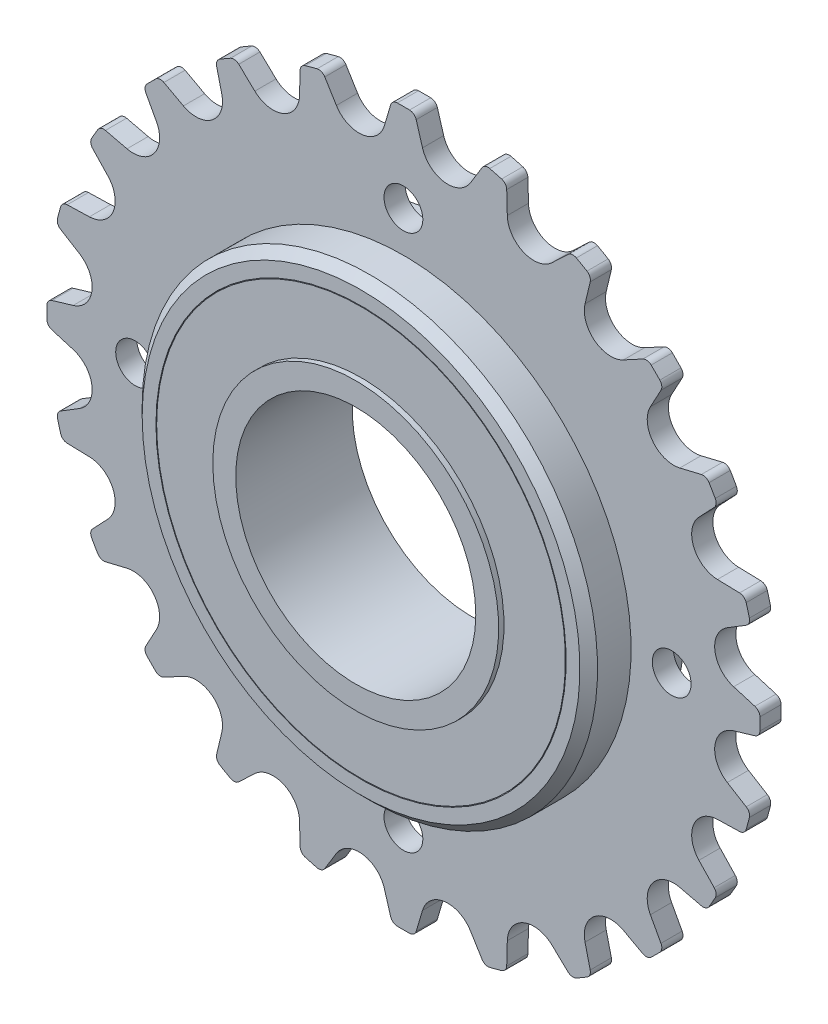
SolidWorks part; units mm, degrees
ref_plane "Front Plane" through (0, 0, 0) normal (0, 0, 1) x (1, 0, 0)
ref_plane "Top Plane" through (0, 0, 0) normal (0, 1, 0) x (1, 0, 0)
ref_plane "Right Plane" through (0, 0, 0) normal (1, 0, 0) x (0, 0, -1)
sketch "Sketch1" plane through (0, 0, 0) normal (0, 1, 0) x (1, 0, 0)
  line L0 (0, 16.3992) -> (0, -18.1929) construction
sketch "Sketch2" plane through (0, 0, 0) normal (0, 1, 0) x (1, 0, 0)
  line L1 (20.25, -7.5) -> (28.95, -7.5)
  line L2 (28.95, -7.5) -> (28.95, -2.5)
  line L3 (28.95, -2.5) -> (29.05, -2.5)
  line L4 (29.05, -2.5) -> (29.05, -7.5)
  line L5 (29.05, -7.5) -> (31, -7.5)
  line L6 (31, -7.5) -> (32.25, -6.25)
  line L7 (32.25, -6.25) -> (32.25, -1.5)
  line L8 (32.25, -1.5) -> (50.5, -1.5)
  line L9 (50.5, -1.5) -> (50.5, 1.5)
  line L10 (50.5, 1.5) -> (32.25, 1.5)
  line L11 (32.25, 1.5) -> (32.25, 6.25)
  line L12 (32.25, 6.25) -> (31, 7.5)
  line L13 (31, 7.5) -> (29.05, 7.5)
  line L14 (29.05, 7.5) -> (29.05, 2.5)
  line L16 (28.95, 2.5) -> (28.95, 7.5)
  line L17 (28.95, 7.5) -> (20.25, 7.5)
  line L18 (0, 0) -> (10.25, 0) construction
  line L19 (29.05, 2.5) -> (28.95, 2.5)
  line L20 (20.25, 7.5) -> (20.25, 8.25)
  line L21 (20.25, 8.25) -> (10.25, 8.25)
  line L22 (10.25, 8.25) -> (10.25, -8.25)
  line L23 (10.25, -8.25) -> (20.25, -8.25)
  line L24 (20.25, -8.25) -> (20.25, -7.5)
  line L26 (0, 200016.3992) -> (0, -200018.1929) construction
  point P27 (28.95, 5)
  dimension "D1" = 15
  dimension "D2" = 20.25
  dimension "D3" = 3
  dimension "D4" = 10
  dimension "D5" = 0.75
  dimension "D6" = 28.95
  dimension "D7" = 0.1
  dimension "D8" = 31
  dimension "D9" = 32.25
  dimension "D10" = 5
  dimension "D11" = 135
  dimension "D12" = 50.5
revolve "Revolve1" add sketch "Sketch2" angle 360 about L0
hole_wizard "M36x2.0 Tapped Hole2" positions "Sketch5" profile "Sketch6" tap size "M36x2.0" standard "ANSI Metric" end condition through all
sketch "Sketch5" plane through (0, 0, 8.25) normal (0, 0, 1) x (1, 0, 0)
  point P0 (0, 0)
sketch "Sketch6" plane through (0, 0, 8.25) normal (1, 0, 0) x (0, -1, 0)
  line L0 (0, 0) -> (0, 16.5)
  line L1 (0, 16.5) -> (17, 16.5)
  line L2 (17, 16.5) -> (17, 0)
  line L5 (17, 0) -> (0, 0)
  line L11 (0, -6.35) -> (0, 107.95) construction
  dimension "Thru Tap Drill Dia." = 34
  dimension "Thru Tap Drill Depth" = 16.5
cosmetic thread "Hole Thread1" parameters "D2"=36
sketch "Sketch7" plane through (0, 0, 0) normal (0, 0, 1) x (1, 0, 0)
  line L0 (0, 0) -> (5.8084, 44.1193) construction
  line L1 (6.7874, 51.5551) -> (6.2979, 47.8372) construction
  line L2 (0, 0) -> (0, 50.5) construction
  line L4 (9.4935, 45.875) -> (11.5164, 49.1693)
  line L5 (2.7033, 46.7689) -> (1.602, 50.4746)
  line L6 (1.602, 50.4746) -> (11.5164, 49.1693) construction
  line L7 (5.8084, 44.1193) -> (6.2979, 47.8372) construction
  circle A0 centre (6.2979, 47.8372) radius 3.75
  circle A1 centre (0, 0) radius 50.5 construction
  circle A2 centre (0, 0) radius 50.5
  dimension "D2" = 7.5
  dimension "D4" = 7.5
  dimension "D1" = 44.5
  dimension "D3" = 10
extrude "Cut-Extrude1" cut sketch "Sketch7" against normal through all both and the other way through all contours L4 A2 L5 A0 | A0 | A0 A2 L5
fillet "Fillet1" radius 1 2 edges at (11.5164, 49.1693, 0) (1.602, 50.4746, 0)
pattern_circular "CirPattern1" count 24 over 360 about axis through (0, 0, 0) along (0, 0, 1) of "Cut-Extrude1", "Fillet1"
sketch "Sketch8" plane through (0, 0, 0) normal (0, 0, 1) x (1, 0, 0)
  line L0 (0, 0) -> (0, 38) construction
  circle A1 centre (0, 38) radius 2.75
  circle A2 centre (38, 0) radius 2.75
  circle A3 centre (0, -38) radius 2.75
  circle A4 centre (-38, 0) radius 2.75
  point P14 (0, 0)
  dimension "D1" = 38
  dimension "D2" = 5.5
  dimension "D3" = 4
extrude "Cut-Extrude2" cut sketch "Sketch8" against normal through all both and the other way through all
